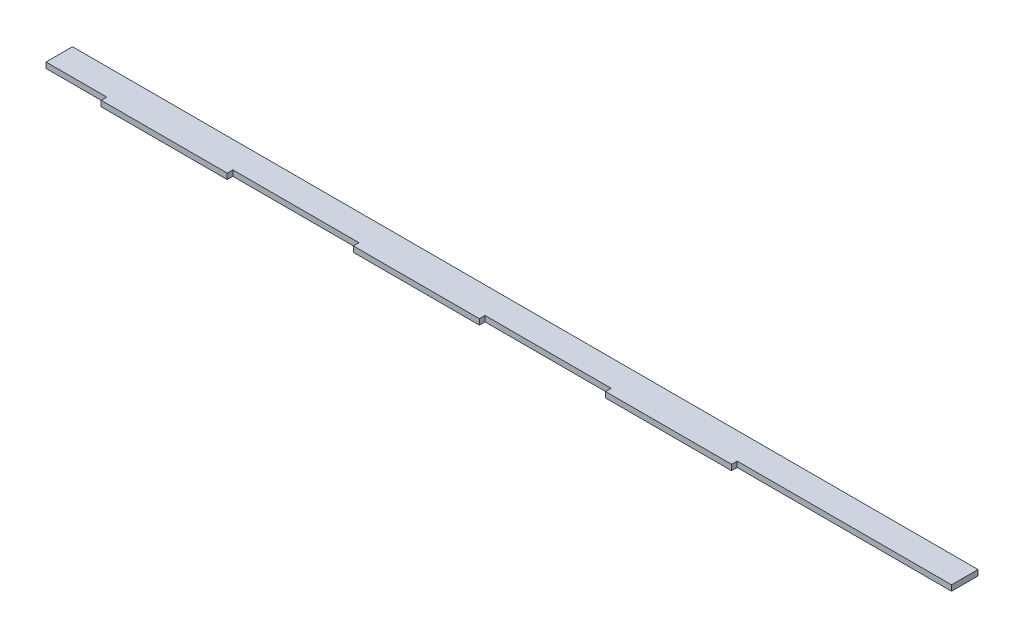
SolidWorks part; units mm, degrees
ref_plane "Front Plane" through (0, 0, 0) normal (0, 0, 1) x (1, 0, 0)
ref_plane "Top Plane" through (0, 0, 0) normal (0, 1, 0) x (1, 0, 0)
ref_plane "Right Plane" through (0, 0, 0) normal (1, 0, 0) x (0, 0, -1)
sketch "Sketch1" plane through (0, 0, 0) normal (0, 1, 0) x (1, 0, 0)
  line L16 (15.5571, 37) -> (15.5571, -3.175) construction
  line L17 (15.5571, 37) -> (15.5571, -3.175) construction
  line L18 (528.5571, 20) -> (528.5571, 0) construction
  line L19 (528.5571, 20) -> (528.5571, 0) construction
  line L32 (15.5571, 0) -> (15.5571, 15)
  line L33 (528.5571, 0) -> (528.5571, 15)
  line L34 (528.5571, 15) -> (15.5571, 15)
  line L44 (407.1286, -3.175) -> (407.1286, 0) construction
  line L45 (335.7, -3.175) -> (335.7, 0) construction
  line L46 (264.2714, -3.175) -> (264.2714, 0) construction
  line L47 (192.8429, -3.175) -> (192.8429, 0) construction
  line L48 (121.4143, -3.175) -> (121.4143, 0) construction
  line L49 (49.9857, -3.175) -> (49.9857, 0) construction
  line L50 (407.1286, -3.175) -> (407.1286, 0)
  line L51 (335.7, -3.175) -> (335.7, 0)
  line L52 (264.2714, -3.175) -> (264.2714, 0)
  line L53 (192.8429, -3.175) -> (192.8429, 0)
  line L54 (121.4143, -3.175) -> (121.4143, 0)
  line L55 (49.9857, -3.175) -> (49.9857, 0)
  line L56 (15.5571, 0) -> (49.9857, 0)
  line L57 (49.9857, -3.175) -> (121.4143, -3.175)
  line L58 (121.4143, 0) -> (192.8429, 0)
  line L59 (192.8429, -3.175) -> (264.2714, -3.175)
  line L60 (264.2714, 0) -> (335.7, 0)
  line L61 (335.7, -3.175) -> (407.1286, -3.175)
  line L62 (407.1286, 0) -> (528.5571, 0)
  dimension "D1" = 15
  dimension "D2" = 15
extrude "Boss-Extrude1" add sketch "Sketch1" along normal blind 3.175
